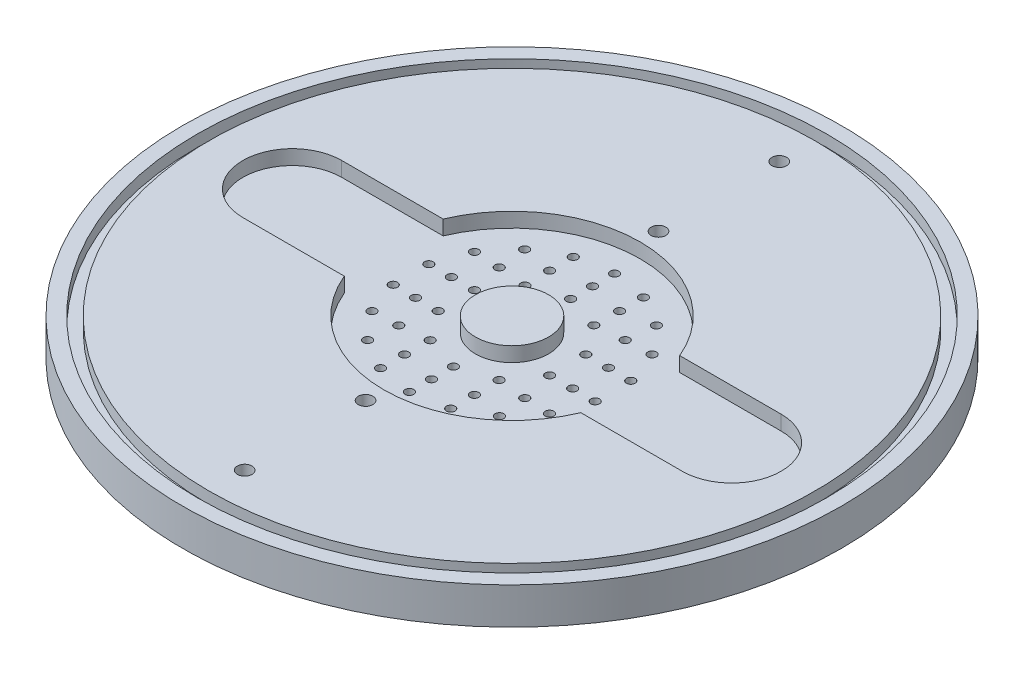
SolidWorks part; units mm, degrees
material "AISI 304"
ref_plane "Front Plane" through (0, 0, 0) normal (0, 0, 1) x (1, 0, 0)
ref_plane "Top Plane" through (0, 0, 0) normal (0, 1, 0) x (1, 0, 0)
ref_plane "Right Plane" through (0, 0, 0) normal (1, 0, 0) x (0, 0, -1)
sketch "Main Shape Profile" plane through (0, 0, 0) normal (0, 0, 1) x (1, 0, 0)
  line L1 (57.15, 0) -> (57.15, 6.35)
  line L2 (57.15, 6.35) -> (0, 6.35)
  line L5 (0, 6.35) -> (0, 0)
  line L6 (0, 0) -> (57.15, 0)
  line L7 (0, 0) -> (0, -50000) construction
  point P4 (0, 0)
  dimension "Kerosene Plate Outer Diameter" = 114.3
  dimension "Kerosene Plate Thickness" = 6.35
revolve "Main Shape" add sketch "Main Shape Profile" angle 360 about L7
sketch "O Rings Profile" plane through (0, 0, 0) normal (0, 0, 1) x (1, 0, 0)
  line L0 (57.15, 6.35) -> (-57.15, 6.35) construction
  line L1 (52.578, 6.35) -> (54.61, 6.35)
  line L2 (52.578, 6.35) -> (52.578, 4.318)
  line L3 (52.578, 4.318) -> (54.61, 4.318)
  line L4 (54.61, 6.35) -> (54.61, 4.318)
  line L5 (-57.15, 0) -> (57.15, 0) construction
  line L6 (52.578, 0) -> (54.61, 0)
  line L7 (52.578, 0) -> (52.578, 2.032)
  line L8 (52.578, 2.032) -> (54.61, 2.032)
  line L9 (54.61, 0) -> (54.61, 2.032)
  line L10 (57.15, 0) -> (57.15, 6.35) construction
  line L11 (0, 0) -> (0, -50000) construction
  dimension "O Ring Depth1" = 2.032
  dimension "O Ring Width" = 2.032
  dimension "O Ring Position" = 2.54
revolve "O-Rings Cutout" cut sketch "O Rings Profile" angle 360 about L11
sketch "Injector Well Profile" plane through (0, 6.35, 0) normal (0, 1, 0) x (1, 0, 0)
  line L0 (-38.1, 0) -> (38.1, 0) construction
  line L1 (-38.1, 8.575) -> (-20.5041, 8.575)
  line L2 (-38.1, -8.575) -> (-20.5041, -8.575)
  line L3 (20.5041, 8.575) -> (38.1, 8.575)
  line L4 (20.5041, -8.575) -> (38.1, -8.575)
  arc A0 (-20.5041, -8.575) -> (20.5041, -8.575) centre (0, 0) ccw
  circle A1 centre (0, 0) radius 6.35
  arc A2 (-38.1, 8.575) -> (-38.1, -8.575) centre (-38.1, 0) ccw
  arc A3 (38.1, -8.575) -> (38.1, 8.575) centre (38.1, 0) ccw
  arc A4 (20.5041, 8.575) -> (-20.5041, 8.575) centre (0, 0) ccw
  point P6 (0, 0)
  dimension "Kerosene Mainfold Diameter" = 44.45
  dimension "Slot Radius" = 17.1501
  dimension "Standoff Diameter" = 12.7
  dimension "Slot Diameter" = 76.2
extrude "Injector Well" cut sketch "Injector Well Profile" against normal blind 2.54
sketch "Dowel Holes Profile" plane through (0, 6.35, 0) normal (0, 1, 0) x (1, 0, 0)
  line L0 (0, -46.355) -> (0, -25.4) construction
  line L1 (0, -25.4) -> (0, -22.225) construction
  line L2 (0, 25.4) -> (0, 22.225) construction
  line L3 (0, 25.4) -> (0, 46.355) construction
  line L4 (0, 46.355) -> (0, 52.578) construction
  line L5 (0, -46.355) -> (0, -52.578) construction
  circle A1 centre (0, 25.4) radius 1.27
  circle A2 centre (0, 46.355) radius 1.27
  circle A3 centre (0, -46.355) radius 1.27
  circle A4 centre (0, -25.4) radius 1.27
  arc A5 (-20.5041, -8.575) -> (20.5041, -8.575) centre (0, 0) ccw construction
  arc A6 (20.5041, 8.575) -> (-20.5041, 8.575) centre (0, 0) ccw construction
  circle A7 centre (0, 0) radius 52.578 construction
  circle A8 centre (0, 0) radius 52.578 construction
  dimension "Dowel Hole Diameter" = 2.54
  dimension "Dowel Placement Inner Diameter" = 50.8
  dimension "Dowel Placement Outer Diameter" = 92.71
extrude "Dowel Holes" cut sketch "Dowel Holes Profile" against normal blind 2.54
sketch "Injector Holes" plane through (0, 3.81, 0) normal (0, 1, 0) x (1, 0, 0)
  line L0 (0, -10.16) -> (0, -13.97) construction
  line L1 (0, -13.97) -> (0, -17.78) construction
  circle A0 centre (0, 0) radius 10.16 construction
  circle A1 centre (0, 0) radius 13.97 construction
  circle A2 centre (0, 0) radius 17.78 construction
  circle A4 centre (0, -17.78) radius 0.7493
  circle A5 centre (0, -13.97) radius 0.7493
  circle A6 centre (0, -10.16) radius 0.7493
  circle A7 centre (-6.0811, -16.7077) radius 0.7493
  circle A11 centre (-11.4288, -13.6203) radius 0.7493
  circle A12 centre (-15.3979, -8.89) radius 0.7493
  circle A13 centre (-17.5099, -3.0875) radius 0.7493
  circle A22 centre (-17.5099, 3.0875) radius 0.7493
  circle A23 centre (-15.3979, 8.89) radius 0.7493
  circle A24 centre (-11.4288, 13.6203) radius 0.7493
  circle A25 centre (-6.0811, 16.7077) radius 0.7493
  circle A26 centre (0, 17.78) radius 0.7493
  circle A27 centre (6.0811, 16.7077) radius 0.7493
  circle A28 centre (11.4288, 13.6203) radius 0.7493
  circle A29 centre (15.3979, 8.89) radius 0.7493
  circle A30 centre (17.5099, 3.0875) radius 0.7493
  circle A31 centre (17.5099, -3.0875) radius 0.7493
  circle A32 centre (15.3979, -8.89) radius 0.7493
  circle A33 centre (11.4288, -13.6203) radius 0.7493
  circle A35 centre (-6.0614, -12.5865) radius 0.7493
  circle A36 centre (-10.9222, -8.7102) radius 0.7493
  circle A37 centre (-13.6197, -3.1086) radius 0.7493
  circle A38 centre (-13.6197, 3.1086) radius 0.7493
  circle A39 centre (-10.9222, 8.7102) radius 0.7493
  circle A40 centre (-6.0614, 12.5865) radius 0.7493
  circle A41 centre (0, 13.97) radius 0.7493
  circle A42 centre (6.0614, 12.5865) radius 0.7493
  circle A43 centre (10.9222, 8.7102) radius 0.7493
  circle A44 centre (13.6197, 3.1086) radius 0.7493
  circle A45 centre (13.6197, -3.1086) radius 0.7493
  circle A46 centre (10.9222, -8.7102) radius 0.7493
  circle A48 centre (-5.9719, -8.2196) radius 0.7493
  circle A49 centre (-9.6627, -3.1396) radius 0.7493
  circle A50 centre (-9.6627, 3.1396) radius 0.7493
  circle A51 centre (-5.9719, 8.2196) radius 0.7493
  circle A52 centre (0, 10.16) radius 0.7493
  circle A53 centre (5.9719, 8.2196) radius 0.7493
  circle A54 centre (9.6627, 3.1396) radius 0.7493
  circle A55 centre (9.6627, -3.1396) radius 0.7493
  circle A56 centre (5.9719, -8.2196) radius 0.7493
  circle A59 centre (6.0614, -12.5865) radius 0.7493
  circle A60 centre (6.0811, -16.7077) radius 0.7493
  point P66 (0, 0)
  point P94 (0, 0)
  point P114 (0, 0)
  dimension "Injector Hole Diameter" = 1.4986
  dimension "Inner Ring Diameter" = 20.32
  dimension "Outer Ring Diameter" = 35.56
  dimension "Outer Ring Holes Num" = 18
  dimension "Middle Ring Holes Num" = 14
  dimension "Inner Ring Holes Num" = 10
extrude "Circular Injector Holes" cut sketch "Injector Holes" against normal through all
sketch "Sketch1" plane through (0, 0, 0) normal (0, -1, 0) x (1, 0, 0)
  circle A0 centre (0, 0) radius 42.9684
split line "Split Line1"
